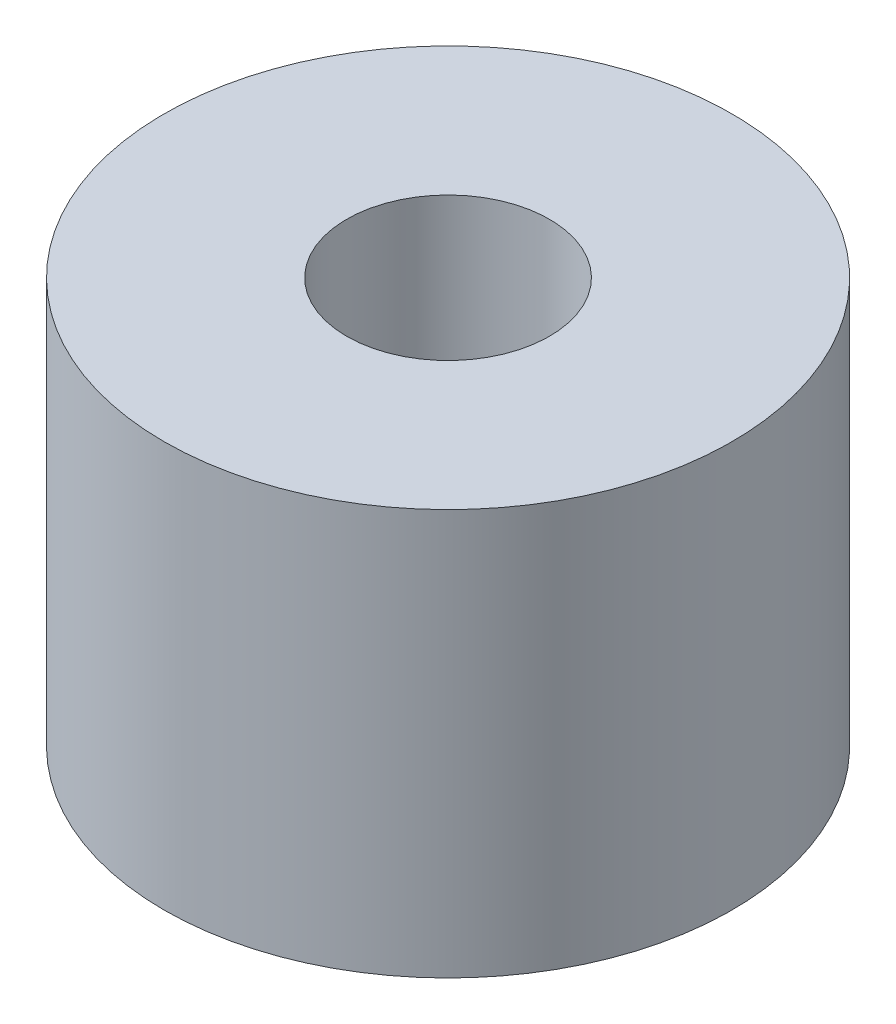
SolidWorks part; units mm, degrees
ref_plane "Plan de face" through (0, 0, 0) normal (0, 0, 1) x (1, 0, 0)
ref_plane "Plan de dessus" through (0, 0, 0) normal (0, 1, 0) x (1, 0, 0)
ref_plane "Plan de droite" through (0, 0, 0) normal (1, 0, 0) x (0, 0, -1)
sketch "Esquisse1" plane through (0, 0, 0) normal (0, 1, 0) x (1, 0, 0)
  circle A0 centre (0, 0) radius 14
  circle A1 centre (0, 0) radius 5
extrude "Boss.-Extru.1" add sketch "Esquisse1" along normal blind 20
